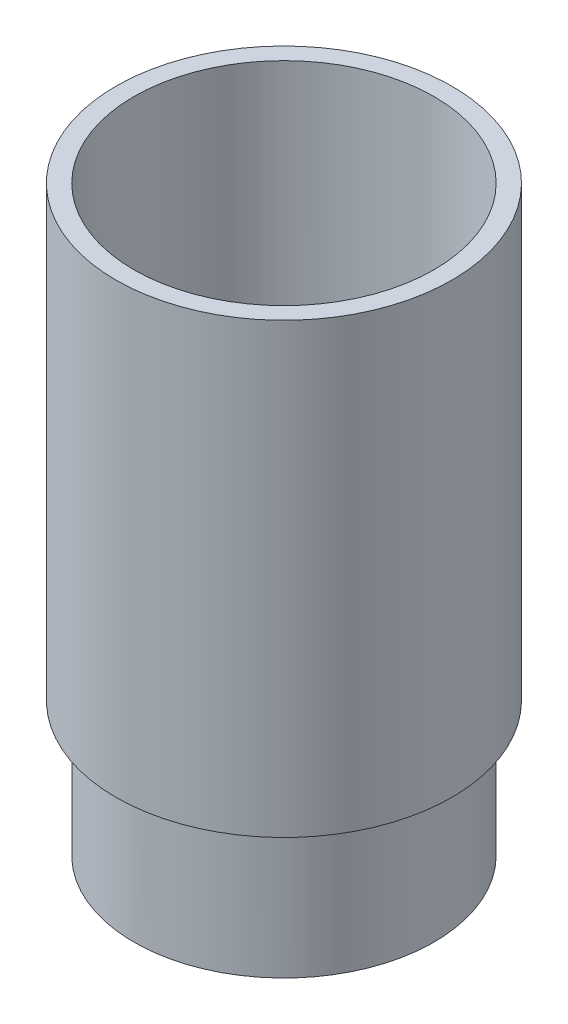
SolidWorks part; units mm, degrees
material "PP Homopolymer"
ref_plane "Front Plane" through (0, 0, 0) normal (0, 0, 1) x (1, 0, 0)
ref_plane "Top Plane" through (0, 0, 0) normal (0, 1, 0) x (1, 0, 0)
ref_plane "Right Plane" through (0, 0, 0) normal (1, 0, 0) x (0, 0, -1)
sketch "Sketch1" plane through (0, 0, 0) normal (0, 1, 0) x (1, 0, 0)
  circle A0 centre (0, 0) radius 37.5
  circle A1 centre (0, 0) radius 33.5
  dimension "D1" = 75
  dimension "D2" = 67
extrude "Boss-Extrude1" add sketch "Sketch1" along normal blind 100
sketch "Sketch2" plane through (0, 0, 0) normal (0, -1, 0) x (1, 0, 0)
  circle A0 centre (0, 0) radius 33.5
  circle A1 centre (0, 0) radius 29.5
  dimension "D1" = 59
extrude "Boss-Extrude2" add sketch "Sketch2" along normal blind 30 and the other way blind 5
